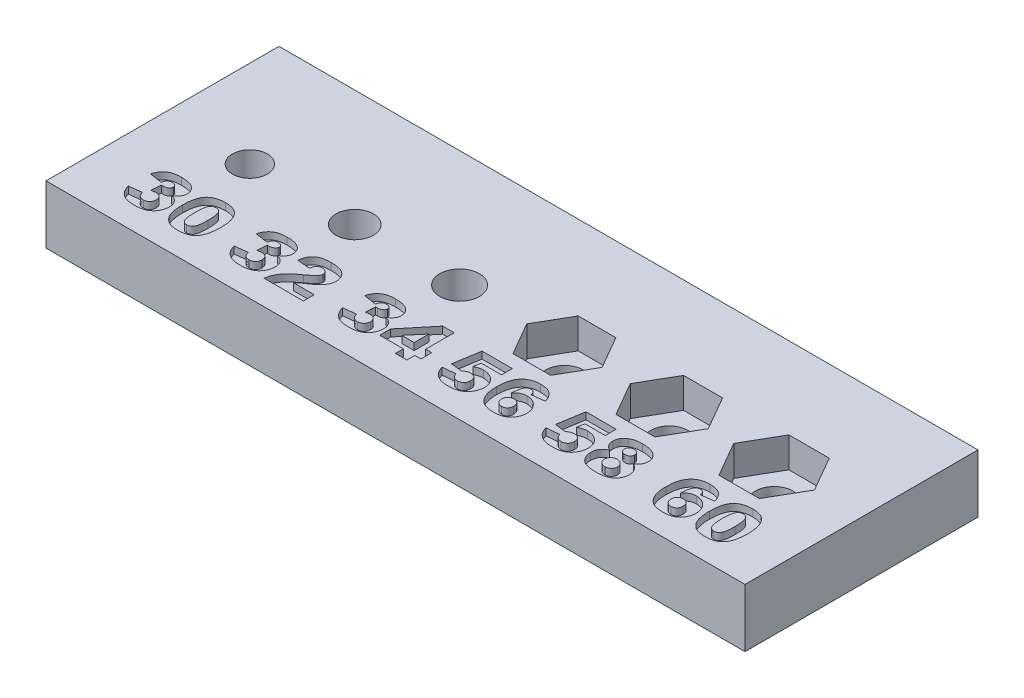
SolidWorks part; units mm, degrees
material "Alloy Steel"
ref_plane "Front Plane" through (0, 0, 0) normal (0, 0, 1) x (1, 0, 0)
ref_plane "Top Plane" through (0, 0, 0) normal (0, 1, 0) x (1, 0, 0)
ref_plane "Right Plane" through (0, 0, 0) normal (1, 0, 0) x (0, 0, -1)
sketch "Sketch1" plane through (0, 0, 0) normal (0, 1, 0) x (1, 0, 0)
  line L1 (0, 0) -> (60, 0)
  line L2 (0, 0) -> (0, 20)
  line L3 (0, 20) -> (60, 20)
  line L4 (60, 0) -> (60, 20)
  dimension "D1" = 60
  dimension "D2" = 20
extrude "Boss-Extrude2" add sketch "Sketch1" against normal blind 5
sketch "Sketch2" plane through (0, 0, 0) normal (0, 1, 0) x (1, 0, 0)
  line L7 (43.5, 10) -> (43.5, 9.61)
  circle A0 centre (7.5, 10) radius 1.5
  circle A1 centre (16.5, 10) radius 1.6
  circle A2 centre (25.5, 10) radius 1.7
  circle A3 centre (34.5, 10) radius 1.6
  circle A4 centre (43.5, 10) radius 1.6
  circle A5 centre (52.5, 10) radius 1.6
  dimension "D2" = 3
  dimension "D4" = 3.2
  dimension "D5" = 3.4
  dimension "D6" = 3.2
  dimension "D7" = 3.2
  dimension "D8" = 3.2
extrude "Cut-Extrude1" cut sketch "Sketch2" against normal blind 5 contours A0 | A1 | A2 | A3 | A4 | A5
sketch "Sketch3" plane through (0, 0, 0) normal (0, 1, 0) x (1, 0, 0)
  line L1 (37.7332, 10) -> (36.1166, 12.8)
  line L2 (36.1166, 12.8) -> (32.8834, 12.8)
  line L3 (32.8834, 12.8) -> (31.2668, 10)
  line L4 (31.2668, 10) -> (32.8834, 7.2)
  line L5 (32.8834, 7.2) -> (36.1166, 7.2)
  line L6 (36.1166, 7.2) -> (37.7332, 10)
  line L7 (46.8486, 10) -> (45.1743, 12.9)
  line L8 (45.1743, 12.9) -> (41.8257, 12.9)
  line L9 (41.8257, 12.9) -> (40.1514, 10)
  line L10 (40.1514, 10) -> (41.8257, 7.1)
  line L11 (41.8257, 7.1) -> (45.1743, 7.1)
  line L12 (45.1743, 7.1) -> (46.8486, 10)
  line L13 (55.9641, 10) -> (54.2321, 13)
  line L14 (54.2321, 13) -> (50.7679, 13)
  line L15 (50.7679, 13) -> (49.0359, 10)
  line L16 (49.0359, 10) -> (50.7679, 7)
  line L17 (50.7679, 7) -> (54.2321, 7)
  line L18 (54.2321, 7) -> (55.9641, 10)
  circle A0 centre (34.5, 10) radius 2.8 construction
  circle A1 centre (43.5, 10) radius 2.9 construction
  circle A2 centre (52.5, 10) radius 3 construction
  point P1 (34.5, 12.8)
  point P10 (34.5, 7.2)
  point P12 (43.5, 12.9)
  point P21 (43.5, 7.1)
  point P23 (52.5, 13)
  point P32 (52.5, 7)
  dimension "D1" = 5.6
  dimension "D2" = 5.8
  dimension "D3" = 6
extrude "Cut-Extrude2" cut sketch "Sketch3" against normal blind 2.6
sketch "Sketch4" plane through (0, 0, 0) normal (0, 1, 0) x (1, 0, 0)
  text T0 "30\r\n" font "Arial Black" height 4
  text T1 "32\r\n" font "Arial Black" height 4
  text T2 "34" font "Arial Black" height 4
  text T3 "56" font "Arial Black" height 4
  text T4 "58" font "Arial Black" height 4
  text T5 "60" font "Arial Black" height 4
  point P1 (0, 0)
extrude "Cut-Extrude3" cut sketch "Sketch4" against normal blind 0.6
